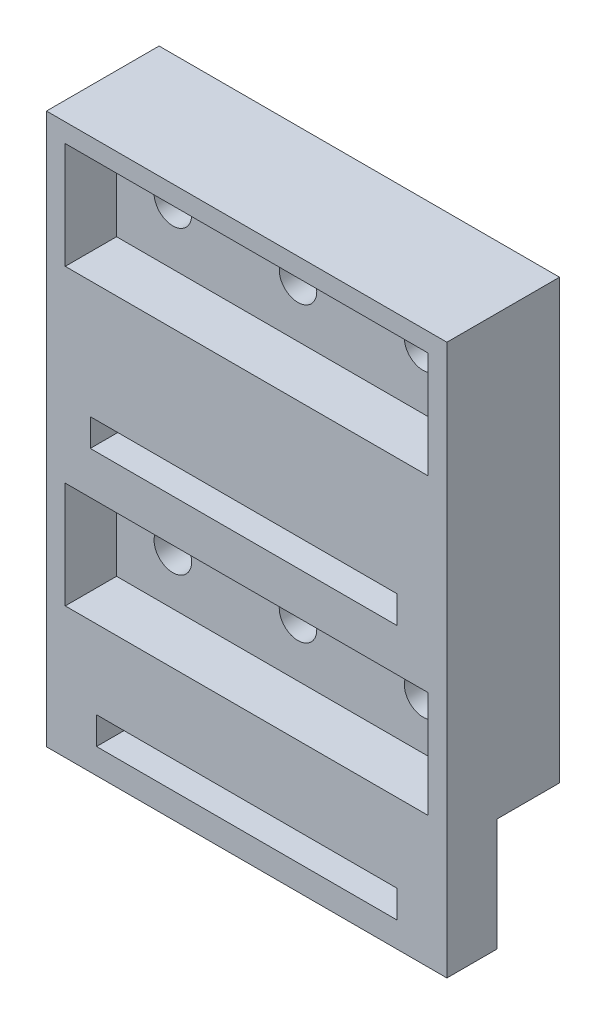
SolidWorks part; units mm, degrees
material "ABS"
ref_plane "Front Plane" through (0, 0, 0) normal (0, 0, 1) x (1, 0, 0)
ref_plane "Top Plane" through (0, 0, 0) normal (0, 1, 0) x (1, 0, 0)
ref_plane "Right Plane" through (0, 0, 0) normal (1, 0, 0) x (0, 0, -1)
sketch "Sketch4" plane through (0, 0, 0) normal (0, 0, 1) x (1, 0, 0)
  line L0 (-16, 17.5) -> (16, -17.5) construction
  line L1 (-16, 17.5) -> (16, 17.5)
  line L2 (-16, 17.5) -> (-16, -17.5)
  line L3 (-16, -17.5) -> (16, -17.5)
  line L4 (16, 17.5) -> (16, -17.5)
  line L5 (16, 17.5) -> (-16, -17.5) construction
  point P4 (0, 0)
  dimension "D1" = 32
  dimension "D2" = 35
extrude "Boss-Extrude1" add sketch "Sketch4" along normal blind 9
shell "Shell1" thickness 1.5
sketch "Sketch5" plane through (0, 0, 4.9) normal (0, 0, 1) x (1, 0, 0)
  line L0 (-14.5, 15) -> (-14.5, -15) construction
  line L1 (-14.5, -15) -> (14.5, -15) construction
  line L2 (14.5, -15) -> (14.5, 15) construction
  line L3 (14.5, 15) -> (-14.5, 15) construction
  line L4 (-14.5, 15) -> (14.5, -15) construction
  line L5 (0, 18.6176) -> (0, -20.2425) construction
  line L6 (12.1043, 0) -> (-43.3409, 0) construction
  circle A0 centre (-10, -12) radius 1.5
  circle A1 centre (10, -12) radius 1.5
  circle A2 centre (0, 11.7) radius 1.5
  circle A3 centre (0, -11.7) radius 1.5
  circle A4 centre (-10, 12) radius 1.5
  circle A5 centre (10, 12) radius 1.5
  point P4 (0, 0)
  dimension "D7" = 3
  dimension "D1" = 29
  dimension "D2" = 30
  dimension "D3" = 20
  dimension "D4" = 3
  dimension "D5" = 10
  dimension "D6" = 23.7
extrude "Cut-Extrude2" cut sketch "Sketch5" against normal blind 9
sketch "Sketch12" plane through (0, 0, 9) normal (0, 0, 1) x (1, 0, 0)
  line L0 (14.5, 0) -> (-14.5, 0)
  line L1 (14.5, -16) -> (14.5, 16) construction
  line L2 (-14.5, 16) -> (-14.5, -16) construction
rib "Rib6" sketch "Sketch12" sketch "Sketch12" thickness 15 parameters "D1"=15
sketch "Sketch13" plane through (0, 0, 0) normal (0, 0, -1) x (-1, 0, 0)
  line L1 (14, -7) -> (-14, -7)
  line L2 (14, -7) -> (14, 1)
  line L3 (14, 1) -> (-14, 1)
  line L4 (-14, -7) -> (-14, 1)
  line L6 (16, 17.5) -> (16, -17.5) construction
  line L7 (-16, -17.5) -> (-16, 17.5) construction
  line L8 (14, -3) -> (-14, -3) construction
  line L10 (-16, 17.5) -> (16, 17.5) construction
  dimension "D1" = 8
  dimension "D2" = 20.5
  dimension "D3" = 2
  dimension "D4" = 2
extrude "Cut-Extrude3" cut sketch "Sketch13" against normal blind 5
sketch "Sketch15" plane through (0, 0, 5) normal (0, 0, -1) x (-1, 0, 0)
  line L1 (12.5, -1.9) -> (-12, -1.9)
  line L2 (12.5, -1.9) -> (12.5, -4.1)
  line L3 (12.5, -4.1) -> (-12, -4.1)
  line L4 (-12, -1.9) -> (-12, -4.1)
  line L6 (14.5, -7) -> (14.5, 1) construction
  line L7 (-14, 1) -> (-14, -7) construction
  dimension "D1" = 2.2
  dimension "D2" = 4.1
  dimension "D3" = 2
  dimension "D4" = 2
extrude "Cut-Extrude4" cut sketch "Sketch15" against normal blind 10
sketch "Sketch16" plane through (0, -17.5, 0) normal (0, -1, 0) x (1, 0, 0)
  line L0 (-16, 9) -> (-16, 0) construction
  line L1 (16, 9) -> (-16, 9)
  line L2 (16, 9) -> (16, 5)
  line L3 (16, 5) -> (-16, 5)
  line L4 (-16, 9) -> (-16, 5)
  dimension "D1" = 4
extrude "Boss-Extrude2" add sketch "Sketch16" along normal blind 9
sketch "Sketch17" plane through (0, 0, 9) normal (0, 0, 1) x (1, 0, 0)
  line L0 (-12.5, -4.1) -> (12, -4.1) construction
  line L1 (12, -24.48) -> (-12, -24.48)
  line L2 (12, -24.48) -> (12, -22.28)
  line L3 (12, -22.28) -> (-12, -22.28)
  line L4 (-12, -24.48) -> (-12, -22.28)
  line L6 (16, -26.5) -> (16, 17.5) construction
  line L7 (-16, 17.5) -> (-16, -26.5) construction
  dimension "D1" = 18.18
  dimension "D2" = 4
  dimension "D3" = 2.2
  dimension "44" = 4
extrude "Cut-Extrude5" cut sketch "Sketch17" against normal blind 10
